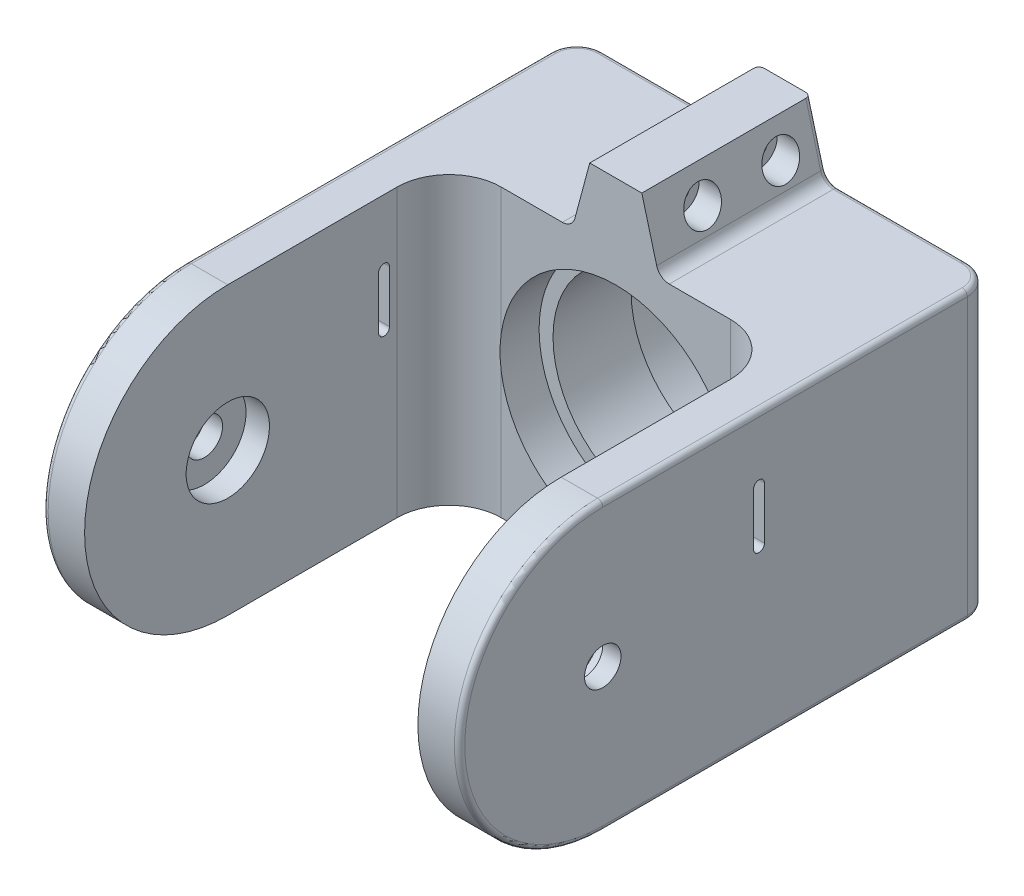
SolidWorks part; units mm, degrees
ref_plane "Front Plane" through (0, 0, 0) normal (0, 0, 1) x (1, 0, 0)
ref_plane "Top Plane" through (0, 0, 0) normal (0, 1, 0) x (1, 0, 0)
ref_plane "Right Plane" through (0, 0, 0) normal (1, 0, 0) x (0, 0, -1)
sketch "Sketch1" plane through (0, 0, 0) normal (0, 0, 1) x (1, 0, 0)
  circle A2 centre (0, 0) radius 44.45
  circle A3 centre (0, 0) radius 44.45 construction
  circle A4 centre (0, 0) radius 39.1
  circle A5 centre (0, 0) radius 38.1 construction
  dimension "D1" = 1
extrude "Centre Hole for L2" add sketch "Sketch1" along normal blind 30 contours A4 | A2
sketch "Sketch2" plane through (0, 0, 30) normal (0, 0, 1) x (1, 0, 0)
  line L0 (0, 48.4974) -> (0, 0) construction
  line L5 (-80, 55) -> (-80, -55)
  line L12 (0, 0) -> (72.986, 0) construction
  line L16 (-80, 55) -> (80, 55)
  line L17 (80, 55) -> (80, -55)
  line L18 (-80, -55) -> (80, -55)
  circle A0 centre (0, 0) radius 44.45
  circle A1 centre (0, 0) radius 44.45 construction
  circle A5 centre (0, 0) radius 44.45
  point P13 (0, 55)
  dimension "D1" = 80
  dimension "D2" = 110
extrude "Main Structure" add sketch "Sketch2" along normal blind 100 and the other way blind 50 separate body
sketch "Sketch3" plane through (-80, 0, 0) normal (-1, 0, 0) x (0, 0, 1)
  line L0 (130, 55) -> (130, -55) construction
  line L1 (130, 55) -> (130, -55)
  line L2 (-20, 55) -> (130, 55) construction
  arc A0 (130, 55) -> (130, -55) centre (130, 0) cw
extrude "Bearing Curve" add sketch "Sketch3" against normal blind 16 contours A0 L1
mirror "Upright Mirror" about plane through (0, 0, 0) normal (1, 0, 0) of "Bearing Curve"
sketch "Sketch6" plane through (-80, 0, 0) normal (-1, 0, 0) x (0, 0, 1)
  circle A0 centre (130, 0) radius 7
  dimension "D1" = 14
extrude "Shaft Hole" cut sketch "Sketch6" against normal up to surface (16 mm away) up to face at (-64, 0, 157.5)
sketch "Sketch4" plane through (0, 55, 0) normal (0, 1, 0) x (1, 0, 0)
  line L0 (0, -110) -> (0, 20) construction
  line L1 (-64, -130) -> (64, -130) construction
  line L2 (-80, 20) -> (80, 20) construction
  line L3 (-64, -130) -> (-64, -65)
  line L4 (-44, -45) -> (44, -45)
  line L5 (-64, -130) -> (64, -130)
  line L6 (64, -130) -> (64, -65)
  arc A0 (-64, -65) -> (-44, -45) centre (-44, -65) cw
  arc A1 (64, -65) -> (44, -45) centre (44, -65) ccw
  point P17 (0, -130)
  point P20 (0, -45)
  dimension "D2" = 20
  dimension "D1" = 65
extrude "Wrist Cutout" cut sketch "Sketch4" against normal through all
sketch "Sketch9" plane through (-64, 0, 0) normal (1, 0, 0) x (0, 0, -1)
  circle A0 centre (-130, 0) radius 16
  dimension "D1" = 32
extrude "Bearing" cut sketch "Sketch9" against normal blind 9
mirror "Bearing Mirror" about plane through (0, 0, 0) normal (1, 0, 0) of "Shaft Hole", "Bearing"
fillet "Fillet2" radius 10 2 edges at (-80, 0, -20) (80, 0, -20)
sketch "Sketch10" plane through (0, 0, -20) normal (0, 0, -1) x (-1, 0, 0)
  line L0 (0, 55) -> (0, 80) construction
  line L1 (70, 55) -> (-70, 55) construction
  line L2 (10, 80) -> (-10, 80)
  line L3 (-10, 80) -> (-16.6987, 55)
  line L4 (-16.6987, 55) -> (16.6987, 55)
  line L5 (10, 80) -> (16.6987, 55)
  dimension "D1" = 25
  dimension "D2" = 10
  dimension "D3" = 75
extrude "Bolt Structure" add sketch "Sketch10" against normal up to surface (65 mm away) up to face at (0, -40.1897, 45)
sketch "Sketch11" plane through (0, 0, 0) normal (1, 0, 0) x (0, 0, -1)
  line L1 (-45, 67.5) -> (20, 67.5) construction
  line L2 (-45, 55) -> (-45, 80) construction
  line L3 (20, 80) -> (20, 55) construction
  circle A1 centre (5, 67.5) radius 3.1
  circle A2 centre (-25, 67.5) radius 3.1
  dimension "D1" = 6.2
  dimension "D2" = 15
  dimension "D3" = 30
extrude "Cut-Extrude6" cut sketch "Sketch11" against normal through all both and the other way through all
sketch "Sketch13" plane through (0, 0, 0) normal (1, 0, 0) x (0, 0, -1)
  circle A0 centre (5, 67.5) radius 7
  circle A1 centre (-25, 67.5) radius 7
  dimension "D1" = 14
extrude "Cut-Extrude8" cut sketch "Sketch13" along normal up to surface (8.3494 mm away) from offset 5
mirror "Mirror8" about plane through (0, 0, 0) normal (0, 1, 0) of "Cut-Extrude6", "Cut-Extrude8", "Bolt Structure"
fillet "Fillet3" radius 5 4 edges at (-16.6987, -55, 12.5) (16.6987, -55, 12.5) (-16.6987, 55, 12.5) (16.6987, 55, 12.5)
fillet "Fillet1" radius 2 22 edges at (-80, 55, 60) (-80, -55, 60) (80, -55, 60) (80, 55, 60) (-80, 0, 185) (-12.8529, -69.353, -20) (-17.4916, -56.0332, -20) (-45.2677, -55, -20) (-77.0711, -55, -17.0711) (-12.8529, 69.353, -20) (-17.4916, 56.0332, -20) (-45.2677, 55, -20) (-77.0711, 55, -17.0711) (12.8529, 69.353, -20) (17.4916, 56.0332, -20) (45.2677, 55, -20) (77.0711, 55, -17.0711) (12.8529, -69.353, -20) (17.4916, -56.0332, -20) (45.2677, -55, -20) (77.0711, -55, -17.0711) (80, 0, 185)
sketch "Sketch14" plane through (-80, 0, 0) normal (-1, 0, 0) x (0, 0, 1)
  line L0 (70, 30) -> (70, 10) construction
  line L1 (72.1, 30) -> (72.1, 10)
  line L2 (67.9, 30) -> (67.9, 10)
  arc A0 (72.1, 30) -> (67.9, 30) centre (70, 30) ccw
  arc A1 (67.9, 10) -> (72.1, 10) centre (70, 10) ccw
  point P2 (70, 20)
  dimension "D1" = 4.2
  dimension "D2" = 20
  dimension "D3" = 10
  dimension "D4" = 70
extrude "Tensioner Slot" cut sketch "Sketch14" against normal up to surface (144 mm away)
mirror "Mirror9" about plane through (0, 0, 0) normal (1, 0, 0) of "Tensioner Slot"
